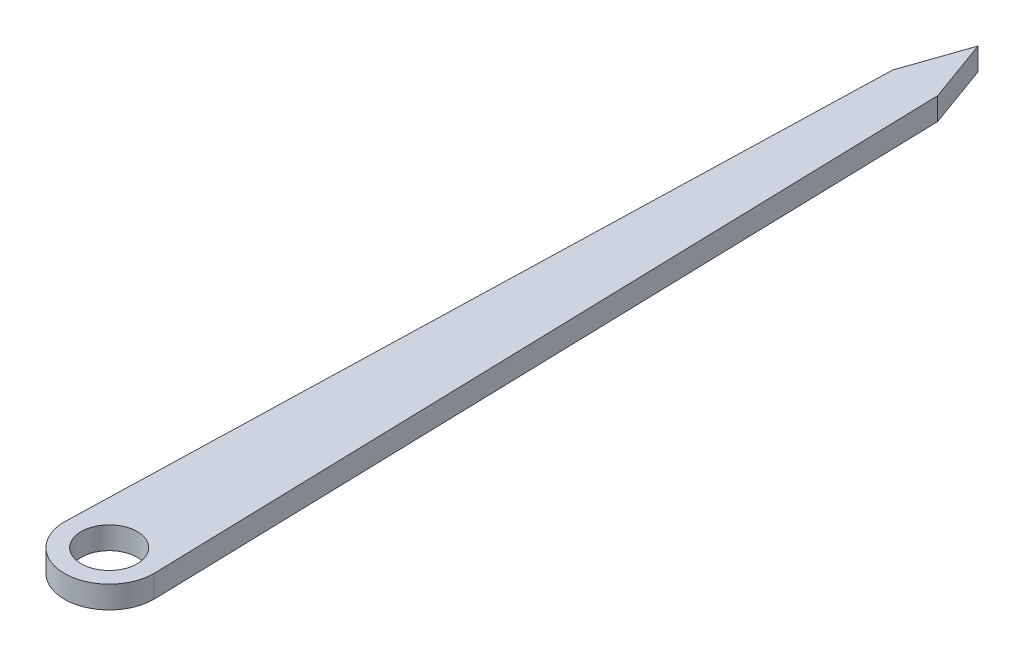
SolidWorks part; units mm, degrees
ref_plane "Přední rovina" through (0, 0, 0) normal (0, 0, 1) x (1, 0, 0)
ref_plane "Horní rovina" through (0, 0, 0) normal (0, 1, 0) x (1, 0, 0)
ref_plane "Pravá rovina" through (0, 0, 0) normal (1, 0, 0) x (0, 0, -1)
sketch "Skica1" plane through (0, 0, 0) normal (0, 1, 0) x (1, 0, 0)
  line L5 (25, 30) -> (195, 30)
  line L6 (0, 0) -> (220, 0)
  line L7 (0, 0) -> (0, 160)
  line L8 (0, 160) -> (220, 160)
  line L9 (220, 0) -> (220, 160)
  line L14 (106, 34) -> (108.0409, 105.9711)
  line L15 (108.0409, 105.9711) -> (110, 111.6422)
  line L16 (114, 34) -> (112.0409, 106)
  line L17 (112.0409, 106) -> (110, 111.6422)
  arc A1 (25, 30) -> (195, 30) centre (110, 30) cw
  circle A2 centre (110, 34) radius 2
  circle A3 centre (110, 34) radius 4
  point P6 (96.8851, 113.9821)
  point P8 (29.0741, 56)
  point P9 (41.2614, 80)
  point P10 (59, 98)
  point P11 (84.2318, 111)
  point P12 (135.7682, 111)
  point P13 (161, 98)
  point P14 (178.7386, 80)
  point P15 (190.9259, 56)
  point P16 (110, 115)
  point P17 (26, 43)
  point P19 (34.4752, 69)
  point P20 (49.69, 89.8974)
  point P21 (69.966, 104.9819)
  point P22 (122.9619, 114.0059)
  point P23 (147.8188, 106.1232)
  point P24 (170.7731, 89.4275)
  point P25 (185.5594, 68.933)
  point P26 (193.9442, 43.3553)
  dimension "D3" = 85
  dimension "D13" = 68
  dimension "D25" = 4
  dimension "D26" = 8
  dimension "D1" = 160
  dimension "D2" = 220
  dimension "D4" = 25
  dimension "D5" = 25
  dimension "D6" = 30
  dimension "D7" = 26
  dimension "D8" = 50
  dimension "D9" = 68
  dimension "D10" = 81
  dimension "D11" = 26
  dimension "D12" = 50
  dimension "D14" = 81
  dimension "D15" = 13
  dimension "D16" = 13
  dimension "D17" = 13
  dimension "D18" = 13
  dimension "D19" = 13
  dimension "D20" = 13
  dimension "D21" = 13
  dimension "D22" = 13
  dimension "D23" = 13
  dimension "D24" = 13
  dimension "D27" = 72
  dimension "D28" = 6
  dimension "D29" = 72
  dimension "D30" = 6
  dimension "D31" = 0
  dimension "D32" = 0
  dimension "D33" = 4
  dimension "D34" = 4
  dimension "D35" = 85
extrude "Přidat vysunutím3" add sketch "Skica1" along normal blind 2 contours A3 L16 L17 L15 L14 | A3 L16 L14 A2
sketch "Skica5" plane through (0, 2, 0) normal (0, 1, 0) x (1, 0, 0)
  circle A0 centre (110, 34) radius 4
  circle A1 centre (110, 34) radius 2
  circle A2 centre (110, 34) radius 2.5
  circle M6 centre (110, 34) radius 2
  dimension "D1" = 8
  dimension "D2" = 4
  dimension "D3" = 5
extrude "Odebrat vysunutím1" cut sketch "Skica5" against normal blind 18 contours A2 M6
